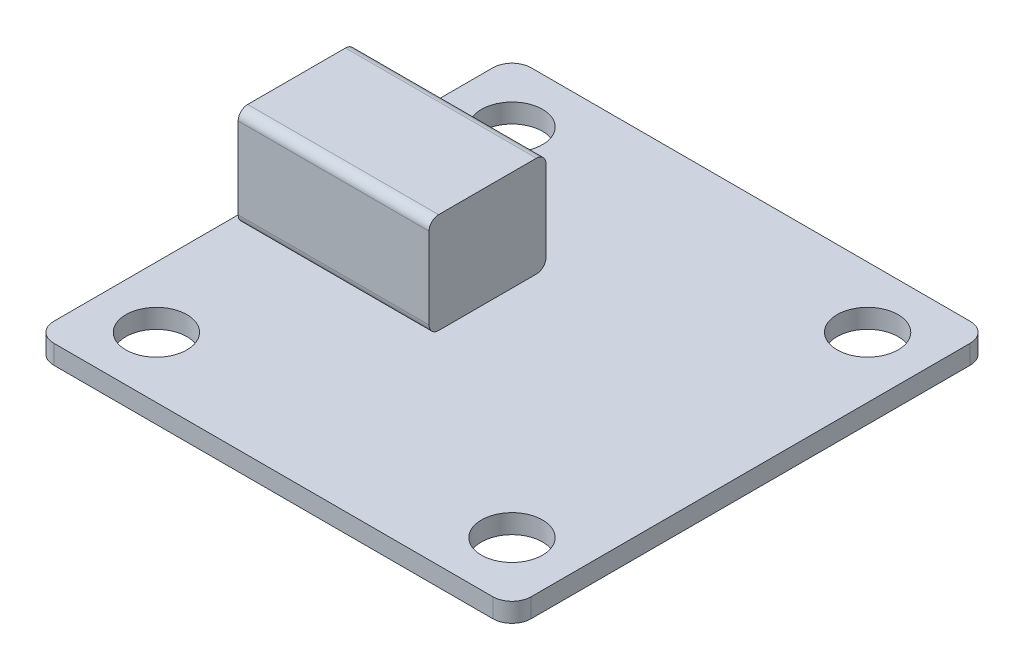
SolidWorks part; units mm, degrees
ref_plane "정면" through (0, 0, 0) normal (0, 0, 1) x (1, 0, 0)
ref_plane "윗면" through (0, 0, 0) normal (0, 1, 0) x (1, 0, 0)
ref_plane "우측면" through (0, 0, 0) normal (1, 0, 0) x (0, 0, -1)
sketch "스케치2" plane through (0, 0, 0) normal (0, 1, 0) x (1, 0, 0)
  line L0 (-37.7363, -24.13) -> (-37.7363, -5.5) construction
  line L1 (-19.11, -24.13) -> (-19.11, -5.5) construction
  line L2 (-37.7363, -5.5) -> (-19.11, -24.13) construction
  line L7 (-19.11, -5.5) -> (-37.7363, -24.13) construction
  line L13 (-40.9231, -2.315) -> (-15.9231, -2.315)
  line L14 (-40.9231, -2.315) -> (-40.9231, -27.315)
  line L19 (-40.9231, -27.315) -> (-15.9231, -27.315)
  line L20 (-15.9231, -2.315) -> (-15.9231, -27.315)
  line L21 (-40.9231, -2.315) -> (-15.9231, -27.315) construction
  line L22 (-40.9231, -27.315) -> (-15.9231, -2.315) construction
  circle A2 centre (-19.11, -24.13) radius 1.6
  circle A3 centre (-37.7363, -24.13) radius 1.6
  circle A4 centre (-37.7363, -5.5) radius 1.6
  circle A5 centre (-19.11, -5.5) radius 1.6
  point P2 (-28.4231, -14.815)
  dimension "D3" = 25
  dimension "D1" = 18.6263
  dimension "D2" = 18.63
  dimension "D4" = 25
extrude "보스-돌출1" add sketch "스케치2" along normal blind 1
fillet "필렛1" radius 1 4 edges at (-40.9231, 0.5, 2.315) (-15.9231, 0.5, 2.315) (-15.9231, 0.5, 27.315) (-40.9231, 0.5, 27.315)
sketch "스케치4" plane through (-40.9231, 0, 0) normal (-1, 0, 0) x (0, 0, 1)
  line L0 (3.315, 1) -> (26.315, 1) construction
  line L1 (11.5362, 1) -> (16.6599, 1)
  line L2 (11.0362, 1.5) -> (11.0362, 5.7578)
  line L3 (11.5362, 6.2578) -> (16.6599, 6.2578)
  line L4 (17.1599, 1.5) -> (17.1599, 5.7578)
  arc A0 (11.5362, 1) -> (11.0362, 1.5) centre (11.5362, 1.5) cw
  arc A1 (16.6599, 1) -> (17.1599, 1.5) centre (16.6599, 1.5) ccw
  arc A2 (11.5362, 6.2578) -> (11.0362, 5.7578) centre (11.5362, 5.7578) ccw
  arc A3 (16.6599, 6.2578) -> (17.1599, 5.7578) centre (16.6599, 5.7578) cw
  point P8 (11.0362, 1)
  dimension "D1" = 0.5
extrude "보스-돌출2" add sketch "스케치4" against normal blind 10 from offset 0.5 offset against normal yes
sketch "스케치5" plane through (-40.4231, 0, 0) normal (-1, 0, 0) x (0, 0, 1)
  point P0 (14.0831, 3.5994)
hole_wizard "Ø3.5 (3.5) 지름 구멍1" positions "스케치5" profile "스케치6" hole size "Ø3.5" standard "Ansi Metric"
sketch "스케치6" plane through (-40.4231, 3.5994, 14.0831) normal (0, 1, 0) x (0, 0, 1)
  line L0 (0, 0) -> (0, 7.0515)
  line L1 (0, 7.0515) -> (1.75, 6)
  line L2 (1.75, 6) -> (1.75, 0.025)
  line L3 (1.75, 0.025) -> (1.775, 0)
  line L5 (1.775, 0) -> (0, 0)
  line L6 (-1.75, 0.025) -> (-1.775, 0) construction
  line L10 (0, 7.0515) -> (-1.75, 6) construction
  line L11 (0, -6.35) -> (0, 107.95) construction
  dimension "구멍 지름" = 3.5
  dimension "구멍 깊이" = 6
  dimension "표면 카운터싱크 지름" = 3.55
  dimension "표면 카운터싱크 각도" = 90
  dimension "드릴 각도" = 118
